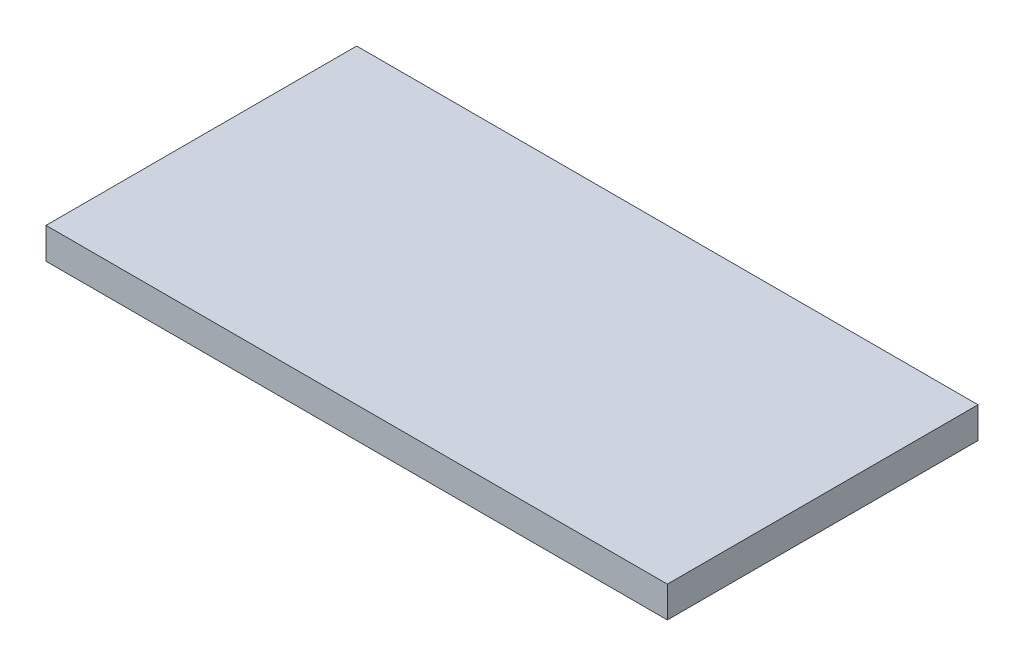
SolidWorks part; units mm, degrees
ref_plane "Front Plane" through (0, 0, 0) normal (0, 0, 1) x (1, 0, 0)
ref_plane "Top Plane" through (0, 0, 0) normal (0, 1, 0) x (1, 0, 0)
ref_plane "Right Plane" through (0, 0, 0) normal (1, 0, 0) x (0, 0, -1)
sketch "Sketch1" plane through (0, 0, 0) normal (0, 1, 0) x (1, 0, 0)
  line L1 (-100, 50) -> (100, 50)
  line L2 (-100, 50) -> (-100, -50)
  line L3 (-100, -50) -> (100, -50)
  line L4 (100, 50) -> (100, -50)
  dimension "D1" = 200
  dimension "D2" = 100
  dimension "D3" = 100
  dimension "D4" = 50
extrude "Boss-Extrude1" add sketch "Sketch1" along normal blind 10
